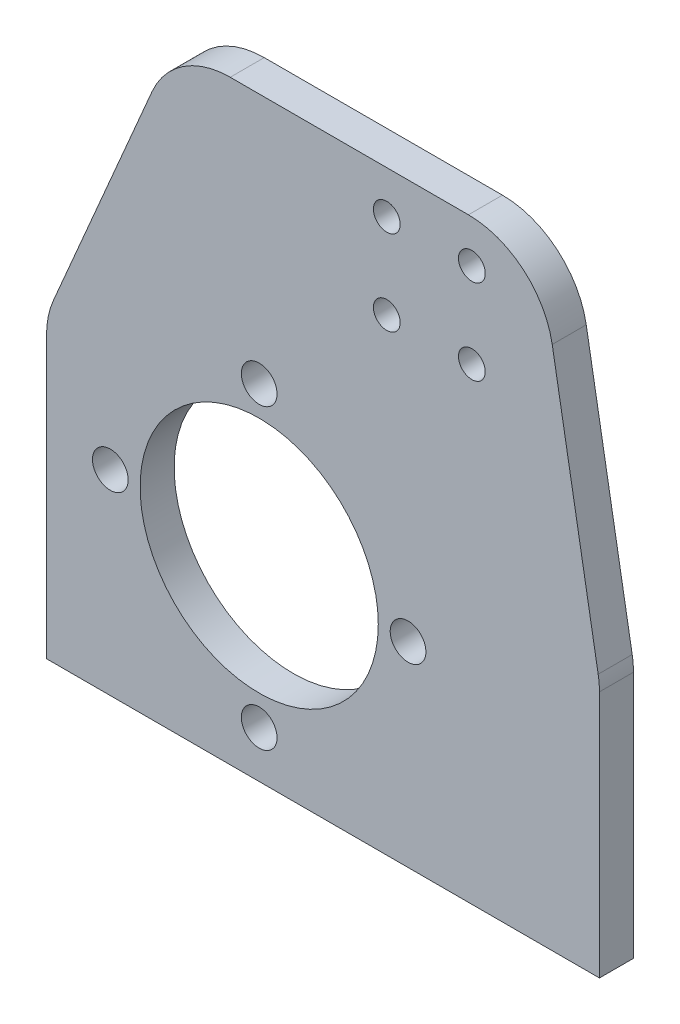
SolidWorks part; units mm, degrees
ref_plane "前视基准面" through (0, 0, 0) normal (0, 0, 1) x (1, 0, 0)
ref_plane "上视基准面" through (0, 0, 0) normal (0, 1, 0) x (1, 0, 0)
ref_plane "右视基准面" through (0, 0, 0) normal (1, 0, 0) x (0, 0, -1)
other "Configuration Table"
sketch "草图1" plane through (0, 0, 0) normal (0, 0, 1) x (1, 0, 0)
  line L1 (0, 0) -> (65, 0)
  line L2 (0, 0) -> (0, -70)
  line L3 (0, -70) -> (65, -70)
  line L4 (65, 0) -> (65, -70)
  dimension "D1" = 65
  dimension "D2" = 70
extrude "凸台-拉伸1" add sketch "草图1" along normal blind 4
sketch "草图2" plane through (0, 0, 4) normal (0, 0, 1) x (1, 0, 0)
  line L0 (25, -70) -> (25, -29.5) construction
  line L1 (0, -70) -> (65, -70) construction
  line L2 (0, -47) -> (65, -47) construction
  line L3 (0, 0) -> (0, -70) construction
  line L4 (65, -70) -> (65, 0) construction
  line L5 (0, -10) -> (65, -10) construction
  line L6 (65, 0) -> (0, 0) construction
  line L7 (45, 0) -> (45, -10) construction
  circle A0 centre (25, -29.5) radius 2.1
  circle A1 centre (7.5, -47) radius 2.1
  circle A2 centre (25, -64.5) radius 2.1
  circle A3 centre (42.5, -47) radius 2.1
  circle A4 centre (40, -5) radius 1.575
  circle A9 centre (50, -5) radius 1.575
  circle A10 centre (50, -15) radius 1.575
  circle A11 centre (40, -15) radius 1.575
  circle A12 centre (25, -47) radius 14
  dimension "D1" = 4.2
  dimension "D3" = 4.2
  dimension "D6" = 3.15
  dimension "D10" = 28
  dimension "D2" = 17.5
  dimension "D4" = 17.5
  dimension "D5" = 23
  dimension "D7" = 10
  dimension "D8" = 5
  dimension "D9" = 5
  dimension "D11" = 20
  dimension "D12" = 20
extrude "切除-拉伸1" cut sketch "草图2" against normal through all
sketch "草图3" plane through (0, 0, 0) normal (0, 0, -1) x (-1, 0, 0)
  line L0 (-15, 0) -> (0, 0)
  line L1 (-65, 0) -> (0, 0) construction
  line L2 (0, 0) -> (0, -35)
  line L3 (0, 0) -> (0, -70) construction
  line L4 (0, -35) -> (-15, 0)
  line L5 (-65, 0) -> (-58, 0)
  line L6 (-58, 0) -> (-65, -40)
  line L7 (-65, -70) -> (-65, 0) construction
  line L8 (-65, -40) -> (-65, 0)
  dimension "D1" = 15
  dimension "D2" = 35
  dimension "D3" = 7
  dimension "D4" = 40
extrude "切除-拉伸2" cut sketch "草图3" against normal through all
fillet "圆角1" radius 10 4 edges at (65, -40, 2) (58, 0, 2) (0, -35, 2) (15, 0, 2)
